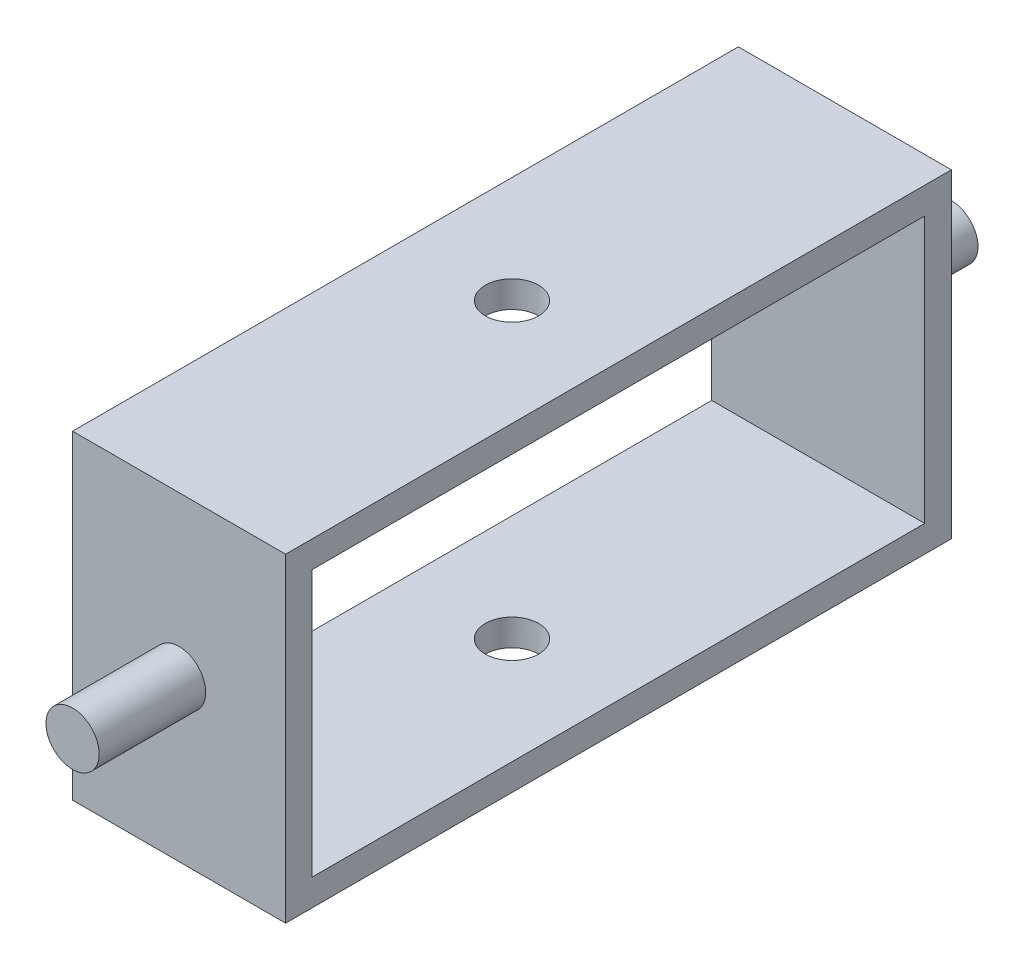
SolidWorks part; units mm, degrees
ref_plane "Спереди" through (0, 0, 0) normal (0, 0, 1) x (1, 0, 0)
ref_plane "Сверху" through (0, 0, 0) normal (0, 1, 0) x (1, 0, 0)
ref_plane "Справа" through (0, 0, 0) normal (1, 0, 0) x (0, 0, -1)
sketch "Эскиз1" plane through (0, 0, 0) normal (0, 0, 1) x (1, 0, 0)
  circle A0 centre (0, 0) radius 5
  dimension "D1" = 10
extrude "Бобышка-Вытянуть1" add sketch "Эскиз1" along normal blind 20
sketch "Эскиз2" plane through (0, 0, 20) normal (0, 0, 1) x (1, 0, 0)
  line L1 (20, -30) -> (-20, -30)
  line L2 (20, -30) -> (20, 30)
  line L3 (20, 30) -> (-20, 30)
  line L4 (-20, -30) -> (-20, 30)
  line L5 (20, -30) -> (-20, 30) construction
  line L6 (20, 30) -> (-20, -30) construction
  point P0 (0, 0)
  dimension "D1" = 60
  dimension "D2" = 40
extrude "Бобышка-Вытянуть2" add sketch "Эскиз2" along normal blind 5
sketch "Эскиз3" plane through (0, 0, 25) normal (0, 0, 1) x (1, 0, 0)
  line L0 (20, -30) -> (20, 30) construction
  line L1 (-20, 30) -> (20, 30)
  line L2 (-20, 30) -> (-20, 25)
  line L3 (-20, 25) -> (20, 25)
  line L4 (20, 30) -> (20, 25)
  line L6 (-20, -30) -> (20, -30)
  line L7 (-20, -30) -> (-20, -25)
  line L8 (-20, -25) -> (20, -25)
  line L9 (20, -30) -> (20, -25)
  dimension "D1" = 5
  dimension "D2" = 5
extrude "Бобышка-Вытянуть3" add sketch "Эскиз3" along normal blind 115
sketch "Эскиз4" plane through (0, 0, 140) normal (0, 0, 1) x (1, 0, 0)
  line L1 (-20, 30) -> (20, 30)
  line L2 (-20, 30) -> (-20, -30)
  line L3 (-20, -30) -> (20, -30)
  line L4 (20, 30) -> (20, -30)
extrude "Бобышка-Вытянуть4" add sketch "Эскиз4" along normal blind 5
sketch "Эскиз5" plane through (0, 0, 145) normal (0, 0, 1) x (1, 0, 0)
  circle A0 centre (0, 0) radius 5
  dimension "D1" = 10
extrude "Бобышка-Вытянуть5" add sketch "Эскиз5" along normal blind 20
sketch "Эскиз6" plane through (0, 30, 0) normal (0, 1, 0) x (1, 0, 0)
  circle A0 centre (0, -82.5) radius 5
  point P4 (0, -82.5)
  dimension "D1" = 10
extrude "Вырез-Вытянуть1" cut sketch "Эскиз6" against normal blind 241
